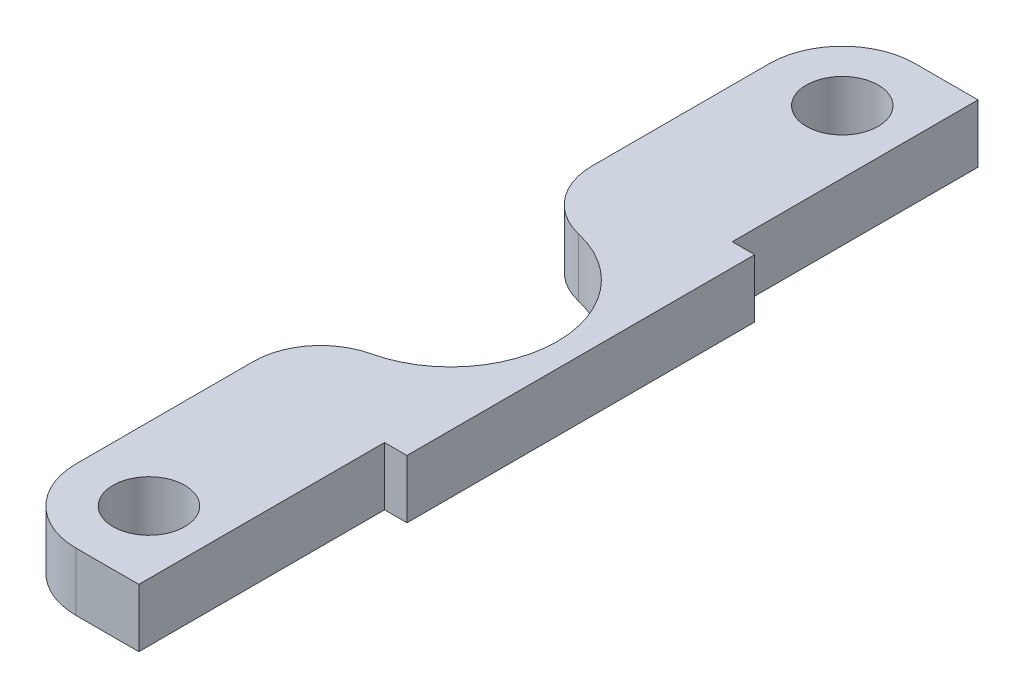
SolidWorks part; units mm, degrees
material "acero"
ref_plane "Alzado" through (0, 0, 0) normal (0, 0, 1) x (1, 0, 0)
ref_plane "Planta" through (0, 0, 0) normal (0, 1, 0) x (1, 0, 0)
ref_plane "Vista lateral" through (0, 0, 0) normal (1, 0, 0) x (0, 0, -1)
sketch "Croquis1" plane through (0, 0, 0) normal (0, 1, 0) x (1, 0, 0)
  line L0 (-3.25, 30.9) -> (-3.25, 0)
  line L1 (2.8, 34.15) -> (2.8, -3.25)
  line L2 (0, 34.15) -> (2.8, 34.15)
  line L3 (0, -3.25) -> (2.8, -3.25)
  circle A0 centre (0, 0) radius 1.6
  circle A1 centre (0, 30.9) radius 1.6
  arc A2 (0, 34.15) -> (-3.25, 30.9) centre (0, 30.9) ccw
  arc A3 (-3.25, 0) -> (0, -3.25) centre (0, 0) ccw
  dimension "D1" = 30.9
  dimension "D2" = 3.2
  dimension "D3" = 6.5
  dimension "D4" = 2.8
extrude "Saliente-Extruir1" add sketch "Croquis1" along normal blind 2.6
sketch "Croquis3" plane through (0, 2.6, 0) normal (0, 1, 0) x (1, 0, 0)
  line L0 (2.8, -3.25) -> (2.8, 34.15) construction
  line L1 (2.8, 23.2) -> (3.8, 23.2)
  line L2 (2.8, 23.2) -> (2.8, 7.7)
  line L3 (2.8, 7.7) -> (3.8, 7.7)
  line L4 (3.8, 23.2) -> (3.8, 7.7)
  line L5 (2.8, 15.45) -> (-3.25, 15.45) construction
  line L6 (-3.25, 30.9) -> (-3.25, 0) construction
  dimension "D1" = 15.5
  dimension "D2" = 1
extrude "Saliente-Extruir2" add sketch "Croquis3" against normal up to surface (2.6 mm away) up to face at (0, 0, 1.6)
sketch "Croquis2" plane through (0, 2.6, 0) normal (0, 1, 0) x (1, 0, 0)
  line L0 (0, 30.9) -> (0, 0) construction
  line L1 (0, 15.45) -> (-2, 15.45) construction
  line L2 (-2, 20.2) -> (-3.25, 20.2)
  line L3 (-3.25, 30.9) -> (-3.25, 0) construction
  line L4 (-3.25, 20.2) -> (-3.25, 10.7)
  line L5 (-3.25, 10.7) -> (-2, 10.7)
  arc A0 (-2, 10.7) -> (-2, 20.2) centre (-2, 15.45) ccw
  dimension "D1" = 2
  dimension "D2" = 9.5
extrude "Cortar-Extruir1" cut sketch "Croquis2" against normal through all
fillet "Redondeo1" radius 3 2 edges at (-3.25, 1.3, -10.7) (-3.25, 1.3, -20.2)
